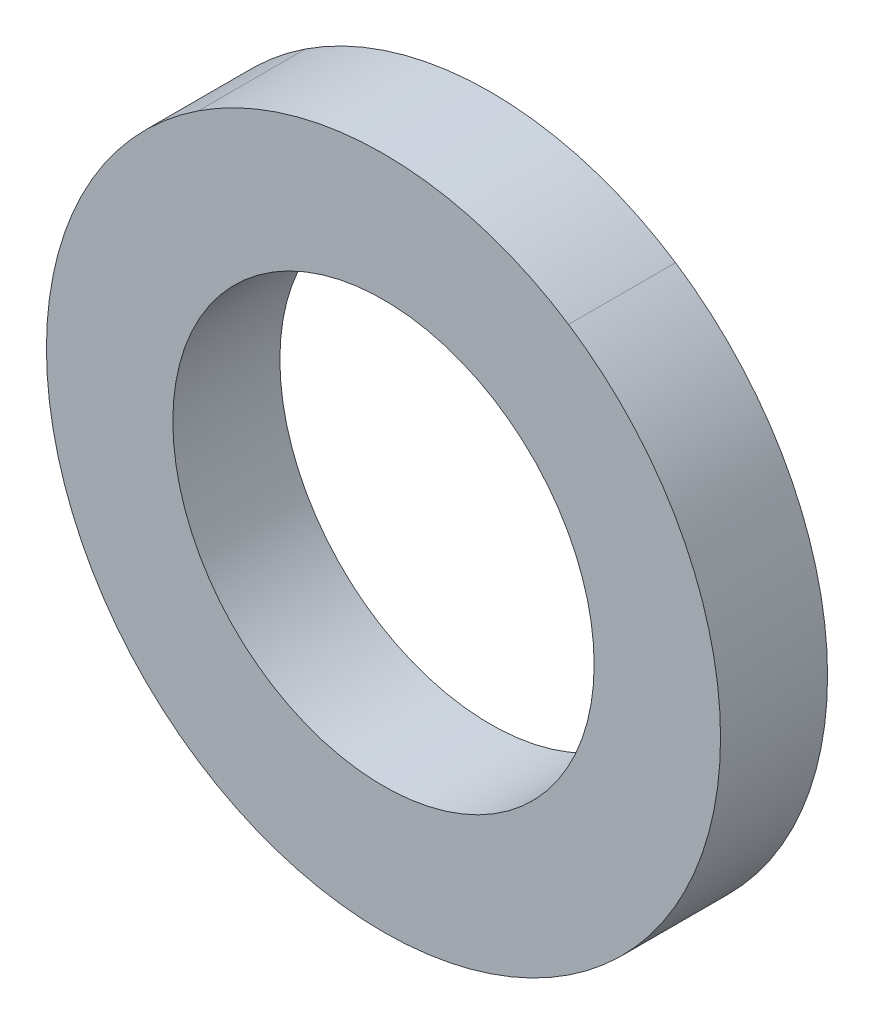
SolidWorks part; units mm, degrees
material "Polyurethane Foam Flexible"
ref_plane "Front Plane" through (0, 0, 0) normal (0, 0, 1) x (1, 0, 0)
ref_plane "Top Plane" through (0, 0, 0) normal (0, 1, 0) x (1, 0, 0)
ref_plane "Right Plane" through (0, 0, 0) normal (1, 0, 0) x (0, 0, -1)
sketch "Sketch1" plane through (0, 0, 0) normal (0, 0, 1) x (1, 0, 0)
  circle A0 centre (0, 0) radius 40
  dimension "D1" = 80
extrude "Boss-Extrude1" add sketch "Sketch1" along normal blind 12.7
sketch "Sketch4" plane through (0, 0, 12.7) normal (0, 0, 1) x (1, 0, 0)
  circle A0 centre (0, 0) radius 25
  point P3 (0, 0)
  dimension "D1" = 50
extrude "Cut-Extrude1" cut sketch "Sketch4" against normal blind 101.6 contours A0
ref_plane "Plane1" through (0, -40, 0) normal (0, -1, 0) x (-1, 0, 0)
ref_plane "Plane2" through (0, -38, 0) normal (0, -1, 0) x (-1, 0, 0)
sketch "Sketch5" plane through (0, -38, 0) normal (0, -1, 0) x (-1, 0, 0)
  line L0 (25, 0) -> (-25, 0) construction
  line L1 (-21.9628, 0) -> (21.9628, 0)
  line L2 (-21.9628, 0) -> (-21.9628, -12.7)
  line L3 (-21.9628, -12.7) -> (21.9628, -12.7)
  line L4 (21.9628, 0) -> (21.9628, -12.7)
  line L5 (-40, -12.7) -> (40, -12.7) construction
  line L6 (0, -12.7) -> (0, 0) construction
split line "Split Line1"
equation "\"OC\"= 80mm"
equation "\"IC\"= 85mm"
equation "\"D1@Sketch1\"=\"OC\""
